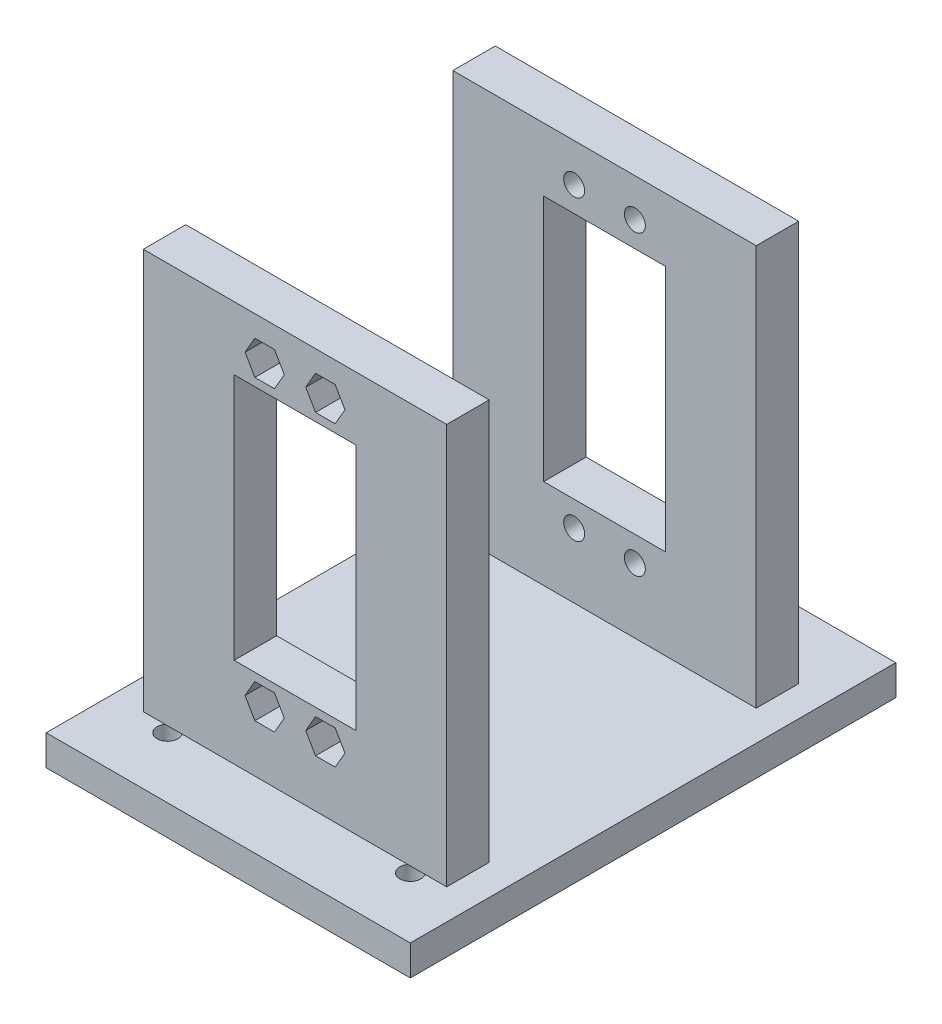
SolidWorks part; units mm, degrees
material "PLA Makeshift"
ref_plane "Front Plane" through (0, 0, 0) normal (0, 0, 1) x (1, 0, 0)
ref_plane "Top Plane" through (0, 0, 0) normal (0, 1, 0) x (1, 0, 0)
ref_plane "Right Plane" through (0, 0, 0) normal (1, 0, 0) x (0, 0, -1)
sketch "Sketch1" plane through (0, 0, 0) normal (0, 1, 0) x (1, 0, 0)
  line L1 (-30, -40) -> (30, -40)
  line L2 (-30, -40) -> (-30, 40)
  line L3 (-30, 40) -> (30, 40)
  line L4 (30, -40) -> (30, 40)
  line L5 (-30, -40) -> (30, 40) construction
  line L6 (-30, 40) -> (30, -40) construction
  point P0 (0, 0)
  dimension "D1" = 80
  dimension "D2" = 60
extrude "Boss-Extrude1" add sketch "Sketch1" along normal mid plane 5
sketch "Sketch2" plane through (0, 2.5, 0) normal (0, 1, 0) x (1, 0, 0)
  line L0 (30, -40) -> (30, 40) construction
  line L2 (-30, 40) -> (-30, -40) construction
  line L3 (-30, -40) -> (30, -40) construction
  circle A0 centre (-20, 30) radius 1.725
  circle A1 centre (20, 30) radius 1.725
  circle A2 centre (20, -30) radius 1.725
  circle A3 centre (-20, -30) radius 1.725
  dimension "D1" = 3.45
  dimension "D2" = 40
  dimension "D3" = 10
  dimension "D4" = 60
  dimension "D5" = 60
  dimension "D6" = 40
  dimension "D7" = 10
  dimension "D8" = 10
  dimension "D9" = 10
extrude "Cut-Extrude1" cut sketch "Sketch2" against normal through all
ref_plane "Plane1" through (0, 0, 22) normal (0, 0, 1) x (1, 0, 0)
sketch "Sketch3" plane through (0, 0, 22) normal (0, 0, 1) x (1, 0, 0)
  line L1 (-25, 2.5) -> (25, 2.5)
  line L2 (-25, 2.5) -> (-25, 68.5)
  line L3 (-25, 68.5) -> (25, 68.5)
  line L4 (25, 2.5) -> (25, 68.5)
  dimension "D1" = 50
  dimension "D2" = 25
  dimension "D3" = 66
  dimension "D4" = 2.5
extrude "Boss-Extrude2" add sketch "Sketch3" along normal blind 7
mirror "Mirror1" about plane through (0, 0, 0) normal (0, 0, 1) of "Boss-Extrude2"
sketch "Sketch4" plane through (0, 0, 29) normal (0, 0, 1) x (1, 0, 0)
  line L1 (-10.025, 58.075) -> (10.025, 58.075)
  line L2 (-10.025, 58.075) -> (-10.025, 17.325)
  line L3 (-10.025, 17.325) -> (10.025, 17.325)
  line L4 (10.025, 58.075) -> (10.025, 17.325)
  dimension "D1" = 20.05
  dimension "D2" = 10.025
  dimension "D3" = 40.75
  dimension "D4" = 17.325
extrude "Cut-Extrude2" cut sketch "Sketch4" against normal through all
sketch "Sketch5" plane through (0, 0, 29) normal (0, 0, 1) x (1, 0, 0)
  circle A0 centre (-5, 62.2) radius 1.725
  circle A1 centre (5, 62.2) radius 1.725
  circle A2 centre (-5, 13.2) radius 1.725
  circle A3 centre (5, 13.2) radius 1.725
  dimension "D9" = 3.45
  dimension "D1" = 5
  dimension "D2" = 5
  dimension "D3" = 13.2
  dimension "D4" = 13.2
  dimension "D5" = 62.2
  dimension "D6" = 62.2
  dimension "D7" = 5
  dimension "D8" = 5
extrude "Cut-Extrude3" cut sketch "Sketch5" against normal through all
sketch "Sketch6" plane through (0, 0, 29) normal (0, 0, 1) x (1, 0, 0)
  line L1 (-1.7668, 62.2) -> (-3.3834, 65)
  line L2 (-3.3834, 65) -> (-6.6166, 65)
  line L3 (-6.6166, 65) -> (-8.2332, 62.2)
  line L4 (-8.2332, 62.2) -> (-6.6166, 59.4)
  line L5 (-6.6166, 59.4) -> (-3.3834, 59.4)
  line L6 (-3.3834, 59.4) -> (-1.7668, 62.2)
  line L7 (1.7668, 62.2) -> (3.3834, 59.4)
  line L8 (3.3834, 59.4) -> (6.6166, 59.4)
  line L9 (6.6166, 59.4) -> (8.2332, 62.2)
  line L10 (8.2332, 62.2) -> (6.6166, 65)
  line L11 (6.6166, 65) -> (3.3834, 65)
  line L12 (3.3834, 65) -> (1.7668, 62.2)
  line L13 (-1.7668, 13.2) -> (-3.3834, 16)
  line L14 (-3.3834, 16) -> (-6.6166, 16)
  line L15 (-6.6166, 16) -> (-8.2332, 13.2)
  line L16 (-8.2332, 13.2) -> (-6.6166, 10.4)
  line L17 (-6.6166, 10.4) -> (-3.3834, 10.4)
  line L18 (-3.3834, 10.4) -> (-1.7668, 13.2)
  line L19 (8.2332, 13.2) -> (6.6166, 16)
  line L20 (6.6166, 16) -> (3.3834, 16)
  line L21 (3.3834, 16) -> (1.7668, 13.2)
  line L22 (1.7668, 13.2) -> (3.3834, 10.4)
  line L23 (3.3834, 10.4) -> (6.6166, 10.4)
  line L24 (6.6166, 10.4) -> (8.2332, 13.2)
  circle A0 centre (-5, 62.2) radius 2.8 construction
  circle A1 centre (5, 62.2) radius 2.8 construction
  circle A2 centre (-5, 13.2) radius 2.8 construction
  circle A3 centre (5, 13.2) radius 2.8 construction
extrude "Cut-Extrude4" cut sketch "Sketch6" against normal blind 4.2
mirror "Mirror3" about plane through (0, 0, 0) normal (0, 0, 1) of "Cut-Extrude4"
